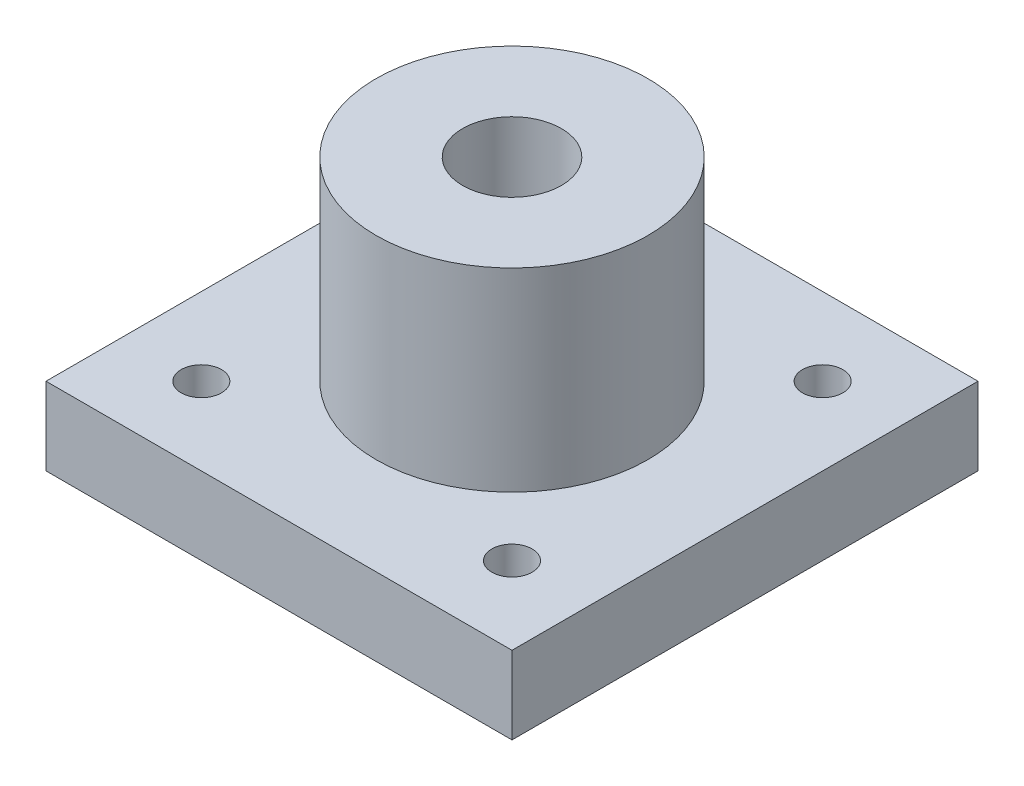
SolidWorks part; units mm, degrees
ref_plane "Front Plane" through (0, 0, 0) normal (0, 0, 1) x (1, 0, 0)
ref_plane "Top Plane" through (0, 0, 0) normal (0, 1, 0) x (1, 0, 0)
ref_plane "Right Plane" through (0, 0, 0) normal (1, 0, 0) x (0, 0, -1)
sketch "Sketch1" plane through (0, 0, 0) normal (0, 1, 0) x (1, 0, 0)
  line L1 (-30, -30) -> (30, -30)
  line L2 (-30, -30) -> (-30, 30)
  line L3 (-30, 30) -> (30, 30)
  line L4 (30, -30) -> (30, 30)
  line L5 (-30, -30) -> (30, 30) construction
  line L6 (-30, 30) -> (30, -30) construction
  circle A0 centre (-20, 20) radius 2.6
  circle A1 centre (20, 20) radius 2.6
  circle A2 centre (-20, -20) radius 2.6
  circle A3 centre (20, -20) radius 2.6
  point P0 (0, 0)
  dimension "D3" = 5.2
  dimension "D4" = 5.2
  dimension "D5" = 5.2
  dimension "D6" = 5.2
  dimension "D1" = 60
  dimension "D2" = 60
  dimension "D7" = 40
  dimension "D8" = 10
  dimension "D9" = 40
  dimension "D10" = 10
extrude "Boss-Extrude1" add sketch "Sketch1" along normal blind 10
sketch "Sketch2" plane through (0, 10, 0) normal (0, 1, 0) x (1, 0, 0)
  circle A0 centre (0, 0) radius 17.5
  circle A1 centre (0, 0) radius 6.3589
  dimension "D1" = 35
  dimension "D2" = 12.7178
extrude "Boss-Extrude2" add sketch "Sketch2" along normal blind 25
equation "\"Length\"= 60mm'Floating Bearing Mount  Length [mm]"
equation "\"Housing OD\"= 35mm'Floating Bearing Mount  Housing OD [mm]"
equation "\"Housing ID\"= 0.5in'Floating Bearing Mount  Housing ID [mm]"
equation "\"D1@Sketch1\"=\"Length\""
equation "\"D2@Sketch1\"=\"Length\""
equation "\"D1@Sketch2\"=\"Housing OD\""
equation "\"D2@Sketch2\"=\"Housing ID\" +0.0007in"
equation "\"Mounting Hole OD\"= 5.2mm"
equation "\"D3@Sketch1\"=\"Mounting Hole OD\""
equation "\"D4@Sketch1\"=\"Mounting Hole OD\""
equation "\"D5@Sketch1\"=\"Mounting Hole OD\""
equation "\"D6@Sketch1\"=\"Mounting Hole OD\""
